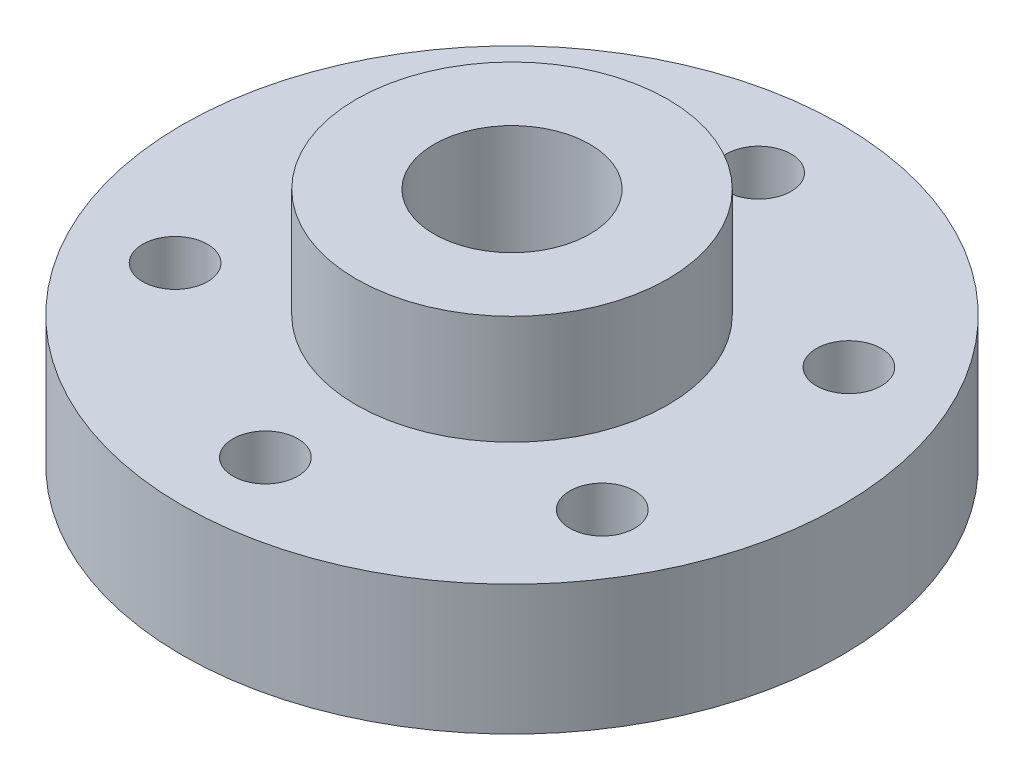
SolidWorks part; units mm, degrees
ref_plane "Plan de face" through (0, 0, 0) normal (0, 0, 1) x (1, 0, 0)
ref_plane "Plan de dessus" through (0, 0, 0) normal (0, 1, 0) x (1, 0, 0)
ref_plane "Plan de droite" through (0, 0, 0) normal (1, 0, 0) x (0, 0, -1)
sketch "Esquisse1" plane through (0, 0, 0) normal (1, 0, 0) x (0, 0, -1)
  line L0 (0, 0) -> (12.7, 0)
  line L1 (12.7, 0) -> (12.7, 5)
  line L2 (12.7, 5) -> (6, 5)
  line L3 (6, 5) -> (6, 9.2)
  line L4 (6, 9.2) -> (0, 9.2)
  line L5 (0, 9.2) -> (0, 0)
  dimension "D1" = 12.7
  dimension "D2" = 5
  dimension "D3" = 4.2
  dimension "D4" = 6
revolve "Révolution1" add sketch "Esquisse1" angle 360 about L5
sketch "Esquisse2" plane through (0, 0, 0) normal (0, -1, 0) x (1, 0, 0)
  circle A0 centre (0, 0) radius 3
  circle A1 centre (0, 0) radius 9.5 construction
  circle A2 centre (0, 9.5) radius 1.25
  circle A3 centre (8.2272, 4.75) radius 1.25
  circle A4 centre (8.2272, -4.75) radius 1.25
  circle A5 centre (0, -9.5) radius 1.25
  circle A6 centre (-8.2272, -4.75) radius 1.25
  circle A7 centre (-8.2272, 4.75) radius 1.25
  point P19 (0, 0)
  dimension "D1" = 6
extrude "Enlèv. mat.-Extru.1" cut sketch "Esquisse2" against normal through all
